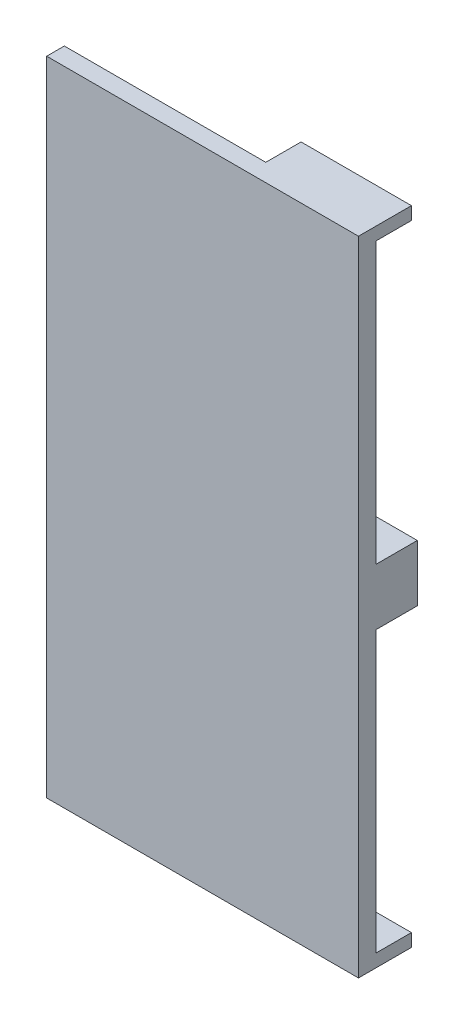
SolidWorks part; units mm, degrees
ref_plane "正面" through (0, 0, 0) normal (0, 0, 1) x (1, 0, 0)
ref_plane "平面" through (0, 0, 0) normal (0, 1, 0) x (1, 0, 0)
ref_plane "右側面" through (0, 0, 0) normal (1, 0, 0) x (0, 0, -1)
sketch "ｽｹｯﾁ1" plane through (0, 0, 0) normal (0, 0, 1) x (1, 0, 0)
  line L1 (47.5727, 6.6919) -> (33.2331, 6.6919) construction
  line L3 (15.7574, 6.6919) -> (42.2574, 6.6919)
  line L6 (42.2574, 61.2919) -> (42.2574, 6.6919)
  line L9 (33.2331, 61.2919) -> (47.5727, 61.2919) construction
  line L10 (42.2574, 61.2919) -> (15.7574, 61.2919)
  line L11 (15.7574, 61.2919) -> (15.7574, 6.6919)
  dimension "D1" = 26.5
  dimension "D2" = 0
  dimension "D3" = 0
extrude "ﾎﾞｽ - 押し出し1" add sketch "ｽｹｯﾁ1" along normal blind 1.5
sketch "ｽｹｯﾁ3" plane through (0, 0, 0) normal (0, 0, -1) x (-1, 0, 0)
  line L0 (-42.2574, 61.2919) -> (-15.7574, 61.2919) construction
  line L1 (-42.2574, 61.2919) -> (-32.8785, 61.2919)
  line L2 (-42.2574, 61.2919) -> (-42.2574, 60.1984)
  line L3 (-42.2574, 60.1984) -> (-32.8785, 60.1984)
  line L4 (-32.8785, 61.2919) -> (-32.8785, 60.1984)
  line L5 (-42.2574, 6.6919) -> (-42.2574, 61.2919) construction
extrude "ﾎﾞｽ - 押し出し2" add sketch "ｽｹｯﾁ3" along normal blind 3
ref_plane "平面1" through (0, 33.9919, 0) normal (0, -1, 0) x (-1, 0, 0)
mirror "ﾐﾗｰ1" about plane through (0, 33.9919, 0) normal (0, -1, 0) of "ﾎﾞｽ - 押し出し2"
sketch "ｽｹｯﾁ4" plane through (0, 0, 0) normal (0, 0, -1) x (-1, 0, 0)
  line L0 (-42.2574, 7.7854) -> (-42.2574, 60.1984) construction
  line L1 (-32.7376, 36.3984) -> (-42.2574, 36.3984)
  line L3 (-32.7376, 31.5854) -> (-42.2574, 31.5854)
  line L4 (-42.2574, 36.3984) -> (-42.2574, 31.5854)
  line L5 (-32.7376, 36.3984) -> (-32.7376, 31.5854)
  line L6 (-47.5727, 31.5854) -> (-50.5727, 31.5854) construction
  line L9 (-23.7286, 40.4919) -> (-23.7286, 27.4919)
  line L12 (-15.7574, 61.2919) -> (-15.7574, 6.6919) construction
  line L13 (-23.7286, 27.4919) -> (-15.7574, 27.4919)
  line L15 (-23.7286, 40.4919) -> (-15.7574, 40.4919)
  line L16 (-15.7574, 27.4919) -> (-15.7574, 40.4919)
  dimension "D1" = 0
extrude "ﾎﾞｽ - 押し出し3" add sketch "ｽｹｯﾁ4" along normal blind 3.5
sketch "ｽｹｯﾁ5" plane through (0, 61.2919, 0) normal (0, 1, 0) x (1, 0, 0)
  line L0 (32.8785, 3) -> (42.2574, 3) construction
  line L1 (32.8785, 3) -> (42.2574, 3)
  line L2 (32.8785, 3) -> (32.8785, 0.1)
  line L3 (32.8785, 0.1) -> (42.2574, 0.1)
  line L4 (42.2574, 3) -> (42.2574, 0.1)
  line L5 (42.2574, -1.5) -> (42.2574, 3) construction
  line L7 (51.0727, 0) -> (32.5376, 0) construction
  dimension "D1" = 0.1
